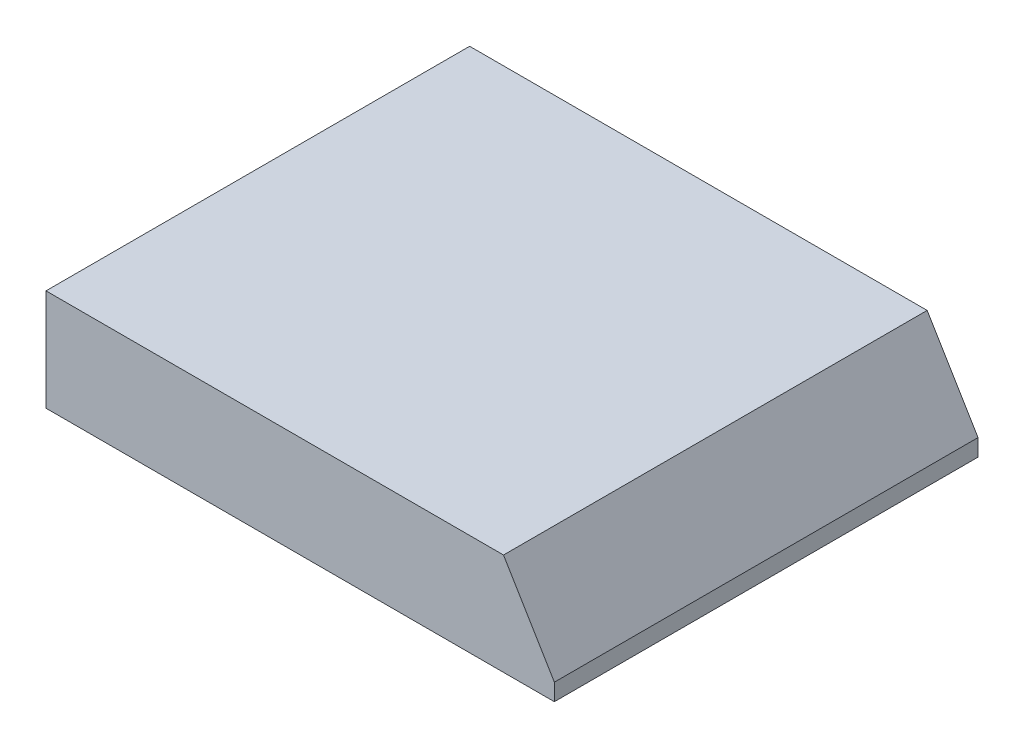
SolidWorks part; units mm, degrees
ref_plane "Front Plane" through (0, 0, 0) normal (0, 0, 1) x (1, 0, 0)
ref_plane "Top Plane" through (0, 0, 0) normal (0, 1, 0) x (1, 0, 0)
ref_plane "Right Plane" through (0, 0, 0) normal (1, 0, 0) x (0, 0, -1)
sketch "Sketch1" plane through (0, 0, 0) normal (0, 0, 1) x (1, 0, 0)
  line L1 (0, 0) -> (60, 0)
  line L2 (0, 0) -> (0, 12)
  line L3 (0, 12) -> (60, 12)
  line L4 (60, 0) -> (60, 12)
  line L5 (0, 0) -> (60, 12) construction
  line L6 (0, 12) -> (60, 0) construction
  point P4 (30, 6)
  dimension "D1" = 60
  dimension "D2" = 12
extrude "Boss-Extrude1" add sketch "Sketch1" along normal blind 50
sketch "Sketch2" plane through (0, 0, 50) normal (0, 0, 1) x (1, 0, 0)
  line L0 (60, 0) -> (60, 12) construction
  line L1 (54, 12) -> (60, 2)
  line L2 (60, 12) -> (0, 12) construction
  line L3 (60, 2) -> (60, 12)
  line L4 (60, 12) -> (54, 12)
  dimension "D1" = 6
  dimension "D2" = 10
extrude "Cut-Extrude1" cut sketch "Sketch2" against normal through all
